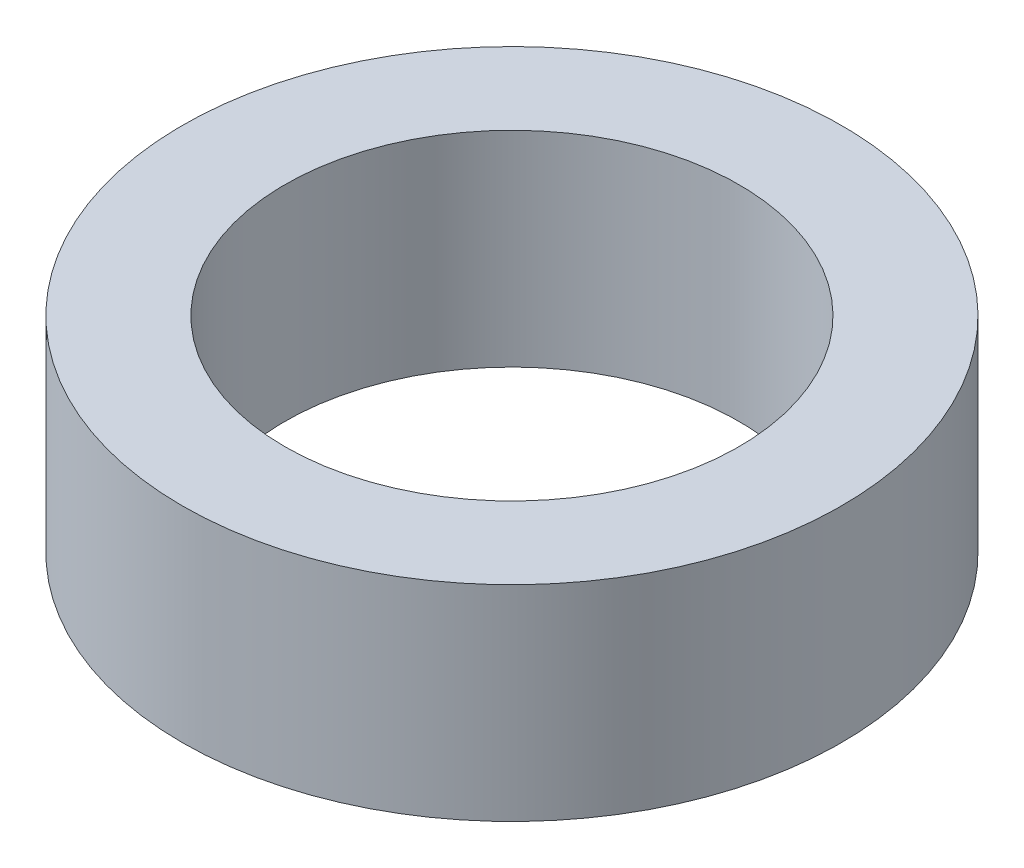
SolidWorks part; units mm, degrees
ref_plane "Front Plane" through (0, 0, 0) normal (0, 0, 1) x (1, 0, 0)
ref_plane "Top Plane" through (0, 0, 0) normal (0, 1, 0) x (1, 0, 0)
ref_plane "Right Plane" through (0, 0, 0) normal (1, 0, 0) x (0, 0, -1)
sketch "Axle Tension Bearing" plane through (0, 0, 0) normal (0, 1, 0) x (1, 0, 0)
  circle A0 centre (0, 0) radius 7.0301
  circle A1 centre (0, 0) radius 10.2051
  dimension "D1" = 14.0603
  dimension "D2" = 20.4103
extrude "Boss-Extrude1" add sketch "Axle Tension Bearing" along normal blind 6.35 contours A1 A0
equation "\"Ball Diameter\"= 1.75in"
equation "\"Sheet Thickness\"= 0.25in"
equation "\"Screw Diameter\"= .17in"
equation "\"Robot Diameter\"= 14in"
equation "\"Castor Screw Diameter\"= 0.22in"
equation "\"Wheel Diameter\" = 4in"
equation "\"Nut Diameter\" = 8.4mm"
equation "\"Nut Height\" = 2.9mm"
equation "\"Screw Height\" = 0.55in"
equation "\"Pulley Diameter\" = 1in"
equation "\"Reactor Height\" = 14in"
equation "\"Elevator Height\" = 11.5in"
equation "\"Elevator Width\" = \"Ball Diameter\" + 0.25in"
equation "\"Elevator Bearing Diameter\" = sqr(2*(\"Sheet Thickness\"^2)) + 0.2in"
equation "\"Elevator Axle Endcap Diameter\" = \"Pulley Diameter\" + 0.25in"
equation "\"Elevator Axle Length\" = \"Elevator Width\" + 8*\"Sheet Thickness\""
equation "\"D1@Axle Tension Bearing\"=\"Elevator Bearing Diameter\""
equation "\"D2@Axle Tension Bearing\"=\"Elevator Bearing Diameter\"+\"Sheet Thickness\""
equation "\"D1@Boss-Extrude1\"=\"Sheet Thickness\""
